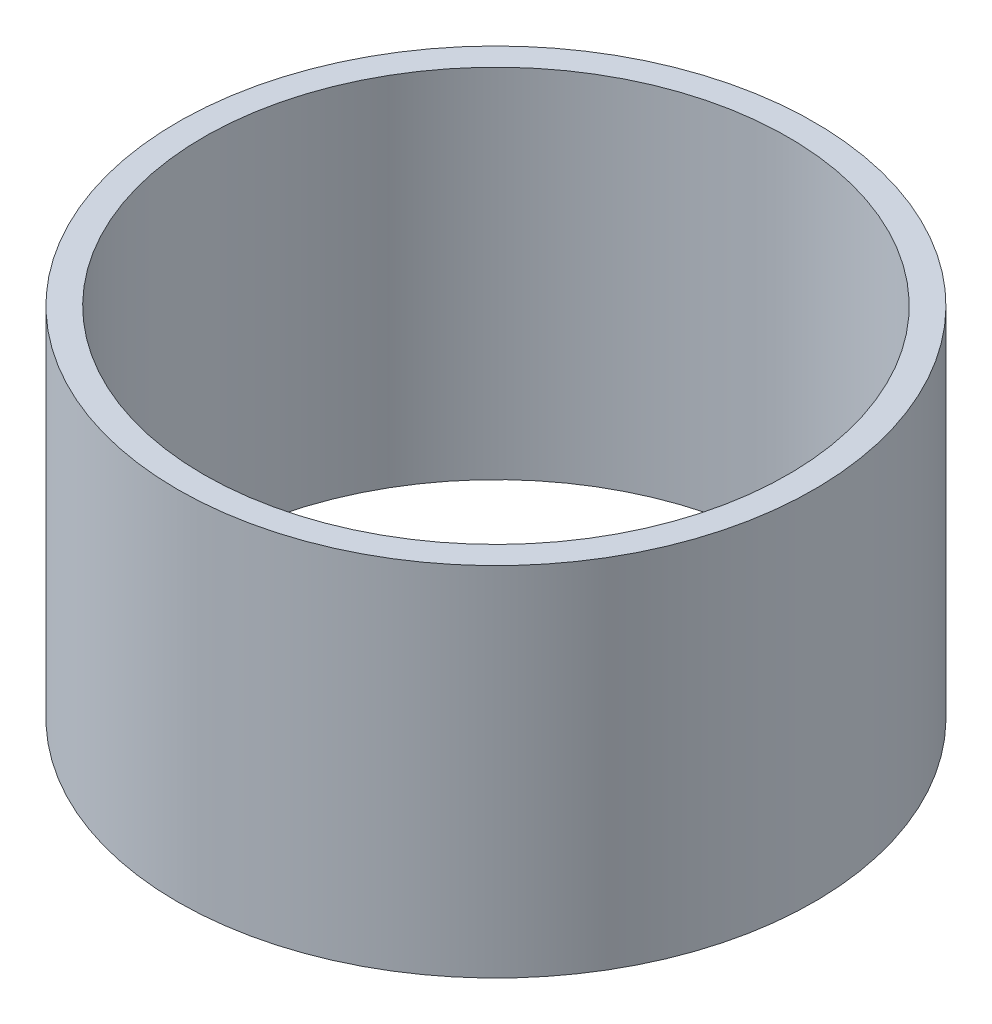
SolidWorks part; units mm, degrees
ref_plane "Alzado" through (0, 0, 0) normal (0, 0, 1) x (1, 0, 0)
ref_plane "Planta" through (0, 0, 0) normal (0, 1, 0) x (1, 0, 0)
ref_plane "Vista lateral" through (0, 0, 0) normal (1, 0, 0) x (0, 0, -1)
sketch "Croquis1" plane through (0, 0, 0) normal (0, 1, 0) x (1, 0, 0)
  circle A0 centre (0, 0) radius 49
  circle A1 centre (0, 0) radius 45
  dimension "D1" = 98
  dimension "D2" = 4
extrude "Saliente-Extruir1" add sketch "Croquis1" along normal blind 55
